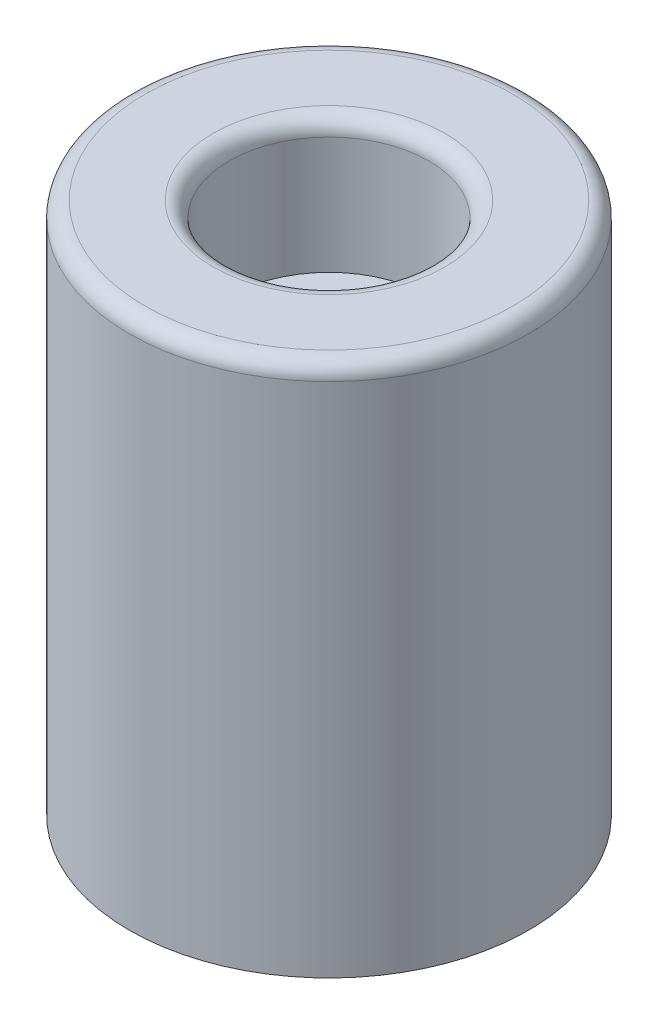
SolidWorks part; units mm, degrees
material "Rubber"
ref_plane "Front" through (0, 0, 0) normal (0, 0, 1) x (1, 0, 0)
ref_plane "Top" through (0, 0, 0) normal (0, 1, 0) x (1, 0, 0)
ref_plane "Right" through (0, 0, 0) normal (1, 0, 0) x (0, 0, -1)
sketch "Sketch1" plane through (0, 0, 0) normal (0, 1, 0) x (1, 0, 0)
  circle A0 centre (0, 0) radius 9.525
  dimension "D1" = 19.05
extrude "Boss-Extrude1" add sketch "Sketch1" along normal blind 25.4
sketch "Sketch2" plane through (0, 25.4, 0) normal (0, 1, 0) x (1, 0, 0)
  circle A0 centre (0, 0) radius 4.7625
  dimension "D1" = 9.525
extrude "Cut-Extrude1" cut sketch "Sketch2" against normal blind 6.35
sketch "Sketch3" plane through (0, 19.05, 0) normal (0, 1, 0) x (1, 0, 0)
  circle A0 centre (0, 0) radius 1.9844
  dimension "D1" = 3.9688
extrude "Cut-Extrude2" cut sketch "Sketch3" against normal through all
fillet "Fillet1" radius 0.762 2 edges at (0, 25.4, 4.7625) (0, 25.4, 9.525)
